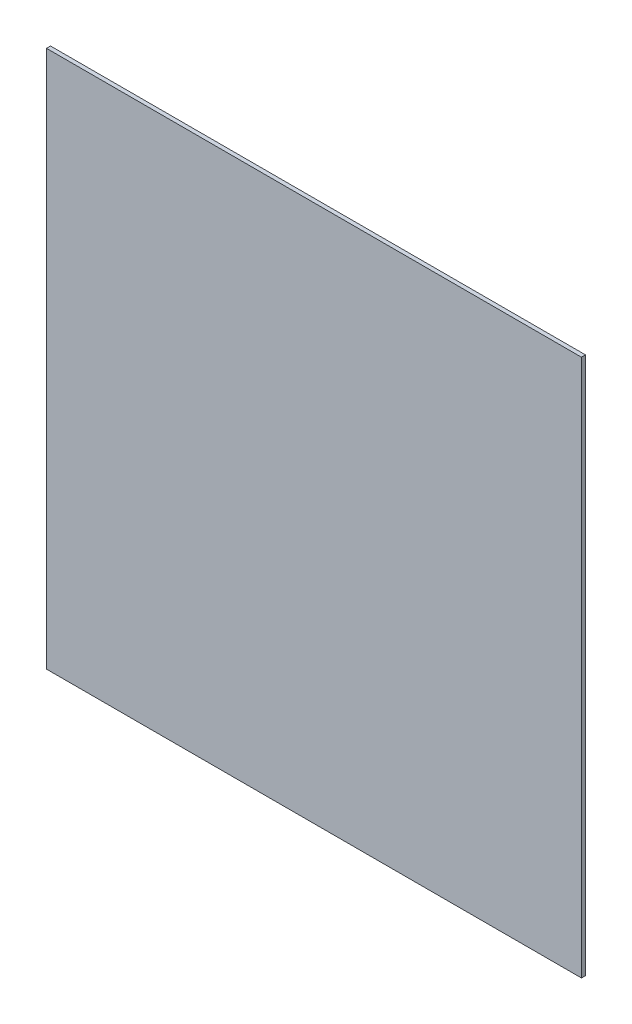
SolidWorks part; units mm, degrees
ref_plane "前基準面" through (0, 0, 0) normal (0, 0, 1) x (1, 0, 0)
ref_plane "上基準面" through (0, 0, 0) normal (0, 1, 0) x (1, 0, 0)
ref_plane "右基準面" through (0, 0, 0) normal (1, 0, 0) x (0, 0, -1)
sketch "草圖1" plane through (0, 0, 0) normal (0, 0, 1) x (1, 0, 0)
  line L1 (-198.5, 199.5) -> (198.5, 199.5)
  line L2 (-198.5, 199.5) -> (-198.5, -199.5)
  line L3 (-198.5, -199.5) -> (198.5, -199.5)
  line L4 (198.5, 199.5) -> (198.5, -199.5)
  line L5 (-198.5, 199.5) -> (198.5, -199.5) construction
  line L6 (-198.5, -199.5) -> (198.5, 199.5) construction
  point P0 (0, 0)
  dimension "D1" = 399
  dimension "D2" = 397
extrude "填料-伸長1" add sketch "草圖1" along normal blind 3
